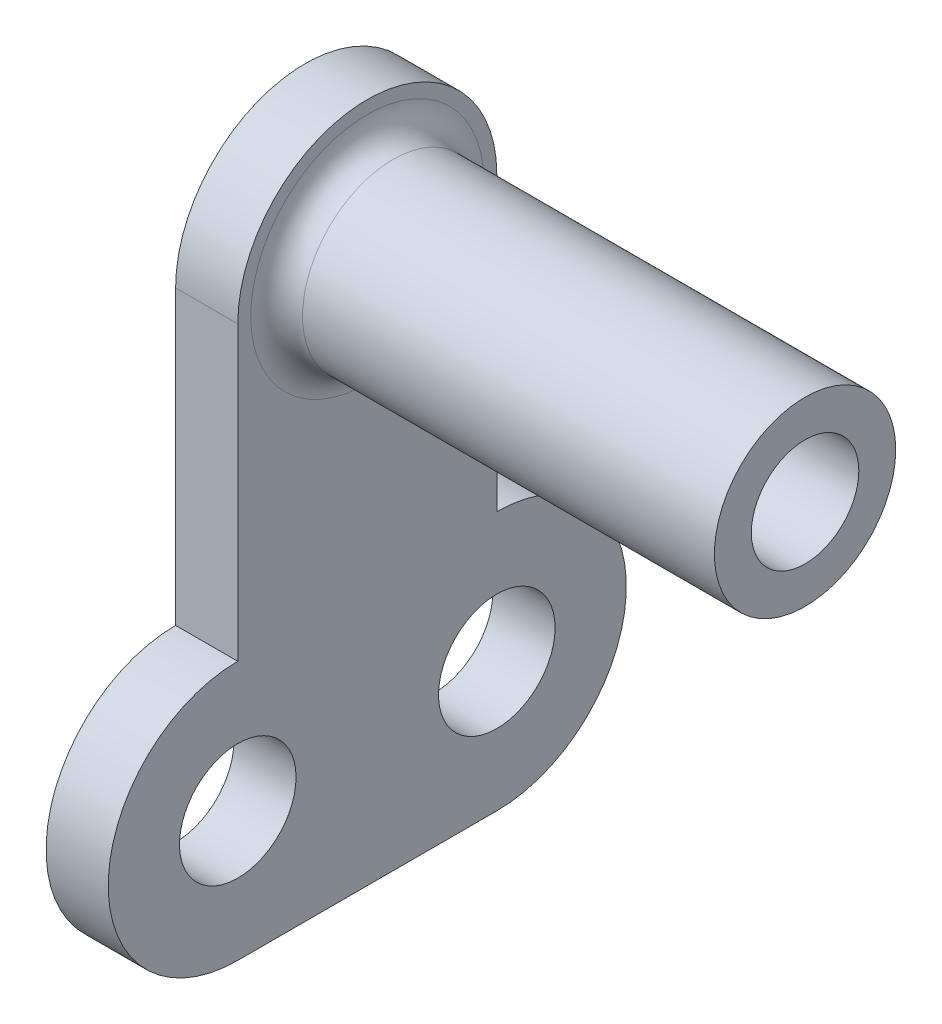
SolidWorks part; units mm, degrees
ref_plane "前视基准面" through (0, 0, 0) normal (0, 0, 1) x (1, 0, 0)
ref_plane "上视基准面" through (0, 0, 0) normal (0, 1, 0) x (1, 0, 0)
ref_plane "右视基准面" through (0, 0, 0) normal (1, 0, 0) x (0, 0, -1)
sketch "草图1" plane through (0, 0, 0) normal (1, 0, 0) x (0, 0, -1)
  line L0 (-5, 0) -> (5, 0)
  line L5 (-5, 10) -> (-5, 21.2822)
  line L6 (5, 10) -> (5, 21.2822)
  circle A2 centre (-5, 5) radius 2.25
  circle A3 centre (5, 5) radius 2.25
  arc A4 (-5, 10) -> (-5, 0) centre (-5, 5) ccw
  arc A6 (5, 0) -> (5, 10) centre (5, 5) ccw
  arc A10 (-5, 21.2822) -> (5, 21.2822) centre (0, 21.2822) cw
  circle A12 centre (0, 21.2822) radius 2.075
  dimension "D3" = 4.5
  dimension "D4" = 5
  dimension "D1" = 10
  dimension "D5" = 4.15
  dimension "D8" = 5
  dimension "D2" = 10
  dimension "D9" = 11.2822
extrude "凸台-拉伸1" add sketch "草图1" along normal blind 2.4
sketch "草图4" plane through (2.4, 0, 0) normal (1, 0, 0) x (0, 0, -1)
  circle A0 centre (0, 21.2822) radius 3.5
  circle A1 centre (0, 21.2822) radius 2.075 construction
  circle A2 centre (0, 21.2822) radius 2.075
  dimension "D1" = 7
extrude "凸台-拉伸2" add sketch "草图4" along normal blind 16.9
fillet "圆角1" radius 1 1 edges at (2.4, 21.2822, -3.5)
sketch "草图5" plane through (0, 0, 0) normal (-1, 0, 0) x (0, 0, 1)
  circle A0 centre (0, 21.2822) radius 1.2
  circle A1 centre (0, 21.2822) radius 2.075
extrude "凸台-拉伸3" add sketch "草图5" against normal blind 4
